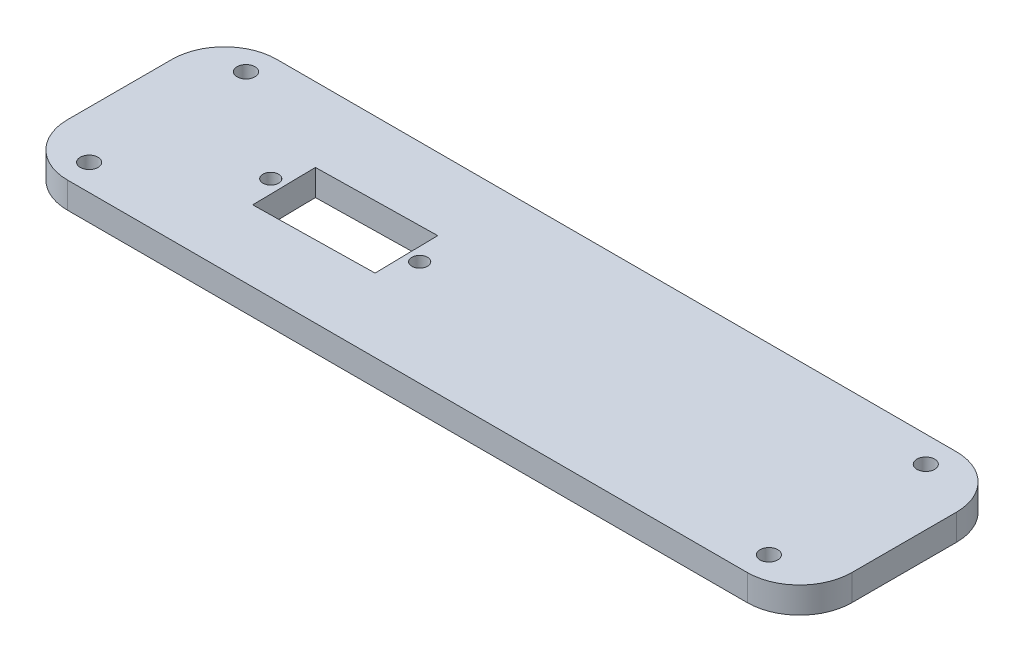
SolidWorks part; units mm, degrees
ref_plane "Front Plane" through (0, 0, 0) normal (0, 0, 1) x (1, 0, 0)
ref_plane "Top Plane" through (0, 0, 0) normal (0, 1, 0) x (1, 0, 0)
ref_plane "Right Plane" through (0, 0, 0) normal (1, 0, 0) x (0, 0, -1)
sketch "Sketch9" plane through (0, 0, 0) normal (0, 1, 0) x (1, 0, 0)
  line L5 (-49.1323, 20) -> (100.8677, 20)
  line L6 (-49.1323, 20) -> (-49.1323, -20)
  line L7 (-49.1323, -20) -> (100.8677, -20)
  line L8 (100.8677, 20) -> (100.8677, -20)
  line L9 (-49.1323, 20) -> (100.8677, -20) construction
  line L10 (-49.1323, -20) -> (100.8677, 20) construction
  point P0 (25.8677, 0)
  dimension "D1" = 40
  dimension "D2" = 150
extrude "Boss-Extrude5" add sketch "Sketch9" along normal blind 5 separate body
sketch "Sketch11" plane through (0, 5, 0) normal (0, 1, 0) x (1, 0, 0)
  circle A0 centre (-40, 15) radius 1.7
  circle A1 centre (90, 15) radius 1.7
  circle A2 centre (90, -15) radius 1.7
  circle A3 centre (-40, -15) radius 1.7
  dimension "D1" = 3.4
  dimension "D3" = 130
  dimension "D5" = 30
  dimension "D2" = 40
  dimension "D4" = 15
extrude "Cut-Extrude6" cut sketch "Sketch11" against normal through all
fillet "Fillet1" radius 10 4 edges at (100.8677, 2.5, 20) (-49.1323, 2.5, 20) (-49.1323, 2.5, -20) (100.8677, 2.5, -20)
sketch "Sketch12" plane through (0, 5, 0) normal (0, 1, 0) x (1, 0, 0)
  line L0 (-1.6323, 20) -> (-1.6323, -20)
  line L4 (-49.1323, 10) -> (-49.1323, -10) construction
  dimension "D1" = 47.5
sketch "Sketch13" plane through (0, 0, 0) normal (0, -1, 0) x (1, 0, 0)
  line L4 (-17.5274, -5.7992) -> (-17.3174, 6.399)
  line L5 (-17.3174, 6.399) -> (5.6791, 6.0032)
  line L6 (5.6791, 6.0032) -> (5.4692, -6.195)
  line L7 (5.4692, -6.195) -> (-17.5274, -5.7992)
  circle A3 centre (8.0738, -0.139) radius 1.5
  circle A4 centre (-19.922, 0.3429) radius 1.5
extrude "Cut-Extrude7" cut sketch "Sketch13" against normal through all
